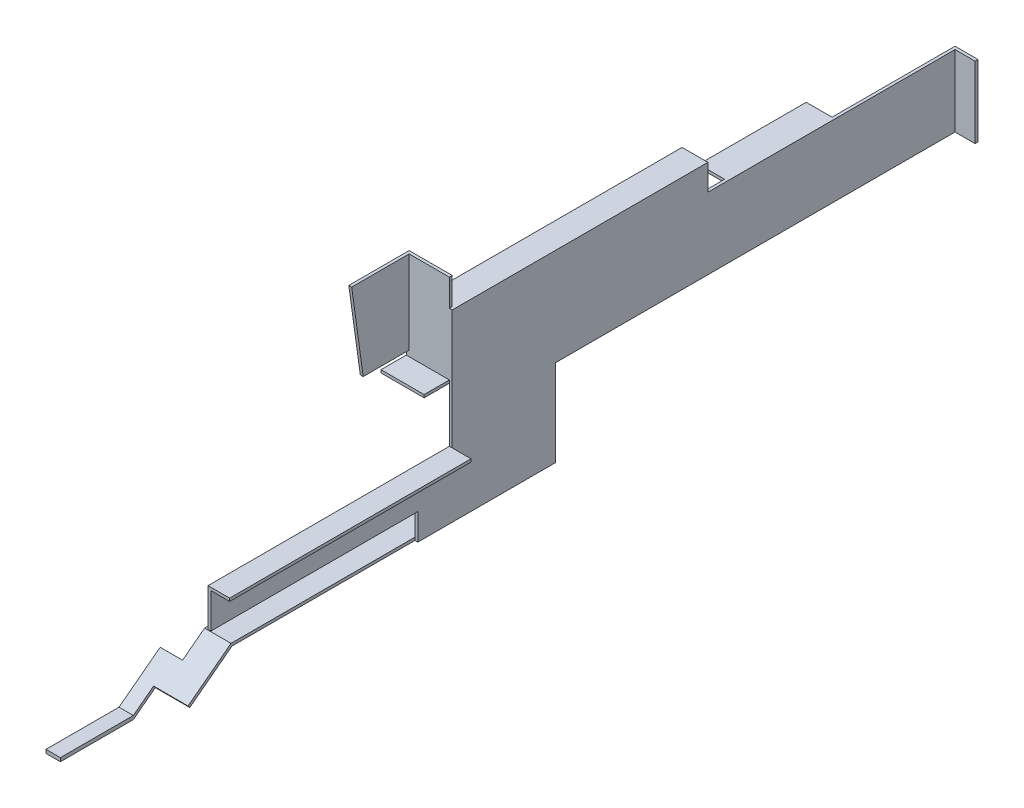
SolidWorks part; units mm, degrees
ref_plane "前视基准面" through (0, 0, 0) normal (0, 0, 1) x (1, 0, 0)
ref_plane "上视基准面" through (0, 0, 0) normal (0, 1, 0) x (1, 0, 0)
ref_plane "右视基准面" through (0, 0, 0) normal (1, 0, 0) x (0, 0, -1)
sketch "草图1" plane through (0, 0, 0) normal (1, 0, 0) x (0, 0, -1)
  line L1 (0, 0) -> (44, 0)
  line L2 (0, 0) -> (0, 6.22)
  line L3 (0, 6.22) -> (44, 6.22)
  line L4 (44, 0) -> (44, 6.22)
  line L5 (0, 0) -> (44, 6.22) construction
  line L6 (0, 6.22) -> (44, 0) construction
  point P4 (22, 3.11)
  dimension "D1" = 6.22
  dimension "D2" = 44
extrude "凸台-拉伸1" add sketch "草图1" along normal blind 0.25
sketch "草图2" plane through (0.25, 0, 0) normal (1, 0, 0) x (0, 0, -1)
  line L1 (44, 6.22) -> (43.75, 6.22)
  line L2 (44, 6.22) -> (44, 0)
  line L3 (44, 0) -> (43.75, 0)
  line L4 (43.75, 6.22) -> (43.75, 0)
  line L5 (44, 6.22) -> (43.75, 0) construction
  line L6 (44, 0) -> (43.75, 6.22) construction
  point P4 (43.875, 3.11)
  dimension "D1" = 0.25
extrude "凸台-拉伸2" add sketch "草图2" along normal blind 1.75
sketch "草图4" plane through (0, 0, 0) normal (-1, 0, 0) x (0, 0, 1)
  line L0 (-44, 6.22) -> (0, 6.22) construction
  line L1 (-44, 0) -> (-10, 0)
  line L2 (-44, 0) -> (-44, 0.25)
  line L3 (-44, 0.25) -> (-10, 0.25)
  line L4 (-10, 0) -> (-10, 0.25)
  line L5 (-44, 0) -> (-10, 0.25) construction
  line L6 (-44, 0.25) -> (-10, 0) construction
  line L7 (-33.3, 6.22) -> (-23.95, 6.22)
  line L8 (-33.3, 6.22) -> (-33.3, 5.97)
  line L9 (-33.3, 5.97) -> (-23.95, 5.97)
  line L10 (-23.95, 6.22) -> (-23.95, 5.97)
  line L11 (-33.3, 6.22) -> (-23.95, 5.97) construction
  line L12 (-33.3, 5.97) -> (-23.95, 6.22) construction
  line L13 (-44, 0) -> (-44, 6.22) construction
  point P4 (-27, 0.125)
  point P10 (-28.625, 6.095)
  dimension "D1" = 0.25
  dimension "D2" = 34
  dimension "D3" = 0.25
  dimension "D4" = 10.7
  dimension "D5" = 9.35
extrude "凸台-拉伸3" add sketch "草图4" along normal blind 2.25
sketch "草图5" plane through (0.25, 0, 0) normal (1, 0, 0) x (0, 0, -1)
  line L0 (43.75, 6.22) -> (0, 6.22) construction
  line L1 (22.25, 6.22) -> (0, 6.22)
  line L2 (22.25, 6.22) -> (22.25, 8.47)
  line L3 (22.25, 8.47) -> (0, 8.47)
  line L4 (0, 6.22) -> (0, 8.47)
  line L5 (22.25, 6.22) -> (0, 8.47) construction
  line L6 (22.25, 8.47) -> (0, 6.22) construction
  line L7 (44, 0) -> (44, 6.22) construction
  line L10 (0, 0) -> (9, 0)
  line L11 (0, 0) -> (0, -7.53)
  line L12 (0, -7.53) -> (9, -7.53)
  line L13 (9, 0) -> (9, -7.53)
  line L14 (0, 0) -> (9, -7.53) construction
  line L15 (0, -7.53) -> (9, 0) construction
  point P4 (11.125, 7.345)
  point P17 (4.5, -3.765)
  dimension "D1" = 21.75
  dimension "D2" = 2.25
  dimension "D3" = 16
  dimension "D4" = 35
extrude "凸台-拉伸4" add sketch "草图5" against normal blind 0.25
sketch "草图6" plane through (0.25, 0, 0) normal (1, 0, 0) x (0, 0, -1)
  line L0 (9, -7.53) -> (9, 0) construction
  line L1 (0, -7.53) -> (-21, -7.53)
  line L2 (0, -7.53) -> (0, -1.93)
  line L3 (0, -1.93) -> (-21, -1.93)
  line L4 (-21, -7.53) -> (-21, -1.93)
  line L5 (0, -7.53) -> (-21, -1.93) construction
  line L6 (0, -1.93) -> (-21, -7.53) construction
  point P4 (-10.5, -4.73)
  dimension "D1" = 30
  dimension "D2" = 5.6
extrude "凸台-拉伸5" add sketch "草图6" against normal blind 0.25
sketch "草图7" plane through (0.25, 0, 0) normal (1, 0, 0) x (0, 0, -1)
  line L0 (9, -7.53) -> (9, 0) construction
  line L1 (-21, -7.53) -> (-3, -7.53)
  line L2 (-21, -7.53) -> (-21, -5.23)
  line L3 (-21, -5.23) -> (-3, -5.23)
  line L4 (-3, -7.53) -> (-3, -5.23)
  line L5 (-21, -7.53) -> (-3, -5.23) construction
  line L6 (-21, -5.23) -> (-3, -7.53) construction
  line L7 (0, -1.93) -> (-21, -1.93) construction
  point P4 (-12, -6.38)
  dimension "D1" = 12
  dimension "D2" = 3.3
extrude "切除-拉伸1" cut sketch "草图7" against normal through all
sketch "草图8" plane through (0.25, 0, 0) normal (1, 0, 0) x (0, 0, -1)
  line L0 (-21, -1.93) -> (-21, -5.23) construction
  line L1 (0, -1.93) -> (-21, -1.93)
  line L2 (0, -1.93) -> (0, -2.18)
  line L3 (0, -2.18) -> (-21, -2.18)
  line L4 (-21, -1.93) -> (-21, -2.18)
  line L5 (0, -1.93) -> (-21, -2.18) construction
  line L6 (0, -2.18) -> (-21, -1.93) construction
  point P4 (-10.5, -2.055)
  dimension "D1" = 0.25
extrude "凸台-拉伸6" add sketch "草图8" along normal blind 1.63
sketch "草图9" plane through (0, 0, 0) normal (-1, 0, 0) x (0, 0, 1)
  line L1 (-9, -7.53) -> (19, -7.53)
  line L2 (-9, -7.53) -> (-9, -7.28)
  line L3 (-9, -7.28) -> (19, -7.28)
  line L4 (19, -7.53) -> (19, -7.28)
  line L5 (-9, -7.53) -> (19, -7.28) construction
  line L6 (-9, -7.28) -> (19, -7.53) construction
  point P4 (5, -7.405)
  dimension "D1" = 0.25
  dimension "D2" = 28
extrude "凸台-拉伸7" add sketch "草图9" along normal blind 2.3
sketch "草图10" plane through (-2.3, 0, 0) normal (-1, 0, 0) x (0, 0, 1)
  line L0 (19, -7.28) -> (24.5, -11.4658)
  line L1 (18.9157, -7.53) -> (24.5, -11.78)
  line L2 (-9, -7.53) -> (19, -7.53) construction
  line L3 (24.5, -11.4658) -> (24.5, -11.78)
  line L4 (19, -7.53) -> (19, -7.28) construction
  line L5 (19, -7.28) -> (-9, -7.28) construction
  line L6 (19, -7.28) -> (19, -7.53)
  line L7 (19, -7.53) -> (18.9157, -7.53)
  dimension "D1" = 0.25
  dimension "D2" = 5.5
  dimension "D3" = 4.5
extrude "凸台-拉伸8" add sketch "草图10" against normal blind 2.3
sketch "草图11" plane through (-2.3, 0, 0) normal (-1, 0, 0) x (0, 0, 1)
  line L0 (24.5, -11.4658) -> (20.9191, -8.7406)
  line L1 (24.5, -11.4658) -> (30.85, -11.4658)
  line L3 (24.5, -11.78) -> (30.85, -11.78)
  line L4 (30.85, -11.4658) -> (30.85, -11.78)
  line L5 (24.5, -11.4658) -> (30.85, -11.78) construction
  line L6 (24.5, -11.78) -> (30.85, -11.4658) construction
  line L7 (24.5, -11.4658) -> (19, -7.28) construction
  line L8 (20.9191, -8.7406) -> (20.7677, -8.9395)
  line L9 (18.9157, -7.53) -> (24.5, -11.78) construction
  line L10 (20.7677, -8.9395) -> (24.5, -11.78)
  point P4 (27.675, -11.6229)
  dimension "D1" = 6.35
  dimension "D2" = 4.5
extrude "凸台-拉伸9" add sketch "草图11" along normal offset from surface (1.95 mm away) 4.5 up to face at (0.25, -0.1869, -7.8462)
sketch "草图12" plane through (0, 4.5467, 3.4603) normal (0, 0.7958, 0.6056) x (1, 0, 0)
  line L0 (-2.3, -19.5283) -> (0, -19.5283) construction
  line L1 (0, -26.6302) -> (-2.3, -26.6302)
  line L2 (0, -26.6302) -> (0, -24.2283)
  line L3 (0, -24.2283) -> (-2.3, -24.2283)
  line L4 (-2.3, -26.6302) -> (-2.3, -24.2283)
  line L5 (0, -26.6302) -> (-2.3, -24.2283) construction
  line L6 (0, -24.2283) -> (-2.3, -26.6302) construction
  point P4 (-1.15, -25.4292)
  dimension "D1" = 4.7
extrude "切除-拉伸2" cut sketch "草图12" against normal through all
sketch "草图13" plane through (0, -11.4658, 0) normal (0, 1, 0) x (1, 0, 0)
  line L0 (-4.25, -24.5) -> (-4.25, -20.9191) construction
  line L1 (-2.3, -30.85) -> (-3, -30.85)
  line L2 (-2.3, -30.85) -> (-2.3, -22.7401)
  line L3 (-2.3, -22.7401) -> (-3, -22.7401)
  line L4 (-3, -30.85) -> (-3, -22.7401)
  line L5 (-2.3, -30.85) -> (-3, -22.7401) construction
  line L6 (-2.3, -22.7401) -> (-3, -30.85) construction
  point P4 (-2.65, -26.795)
  dimension "D1" = 1.25
extrude "切除-拉伸3" cut sketch "草图13" against normal through all and the other way through all
sketch "草图14" plane through (-2.3, 0, 0) normal (1, 0, 0) x (0, 0, -1)
  line L3 (-22.7401, -10.1264) -> (-22.7401, -10.4406)
  line L4 (-22.7401, -10.4406) -> (-22.5886, -10.3253)
  line L5 (-22.5886, -10.3253) -> (-22.7401, -10.1264)
  line L6 (-22.7401, -10.1264) -> (-22.7401, -10.4406)
  line L7 (-22.7401, -10.4406) -> (-22.5886, -10.3253)
  line L8 (-22.5886, -10.3253) -> (-22.7401, -10.1264)
  dimension "D1" = 0
extrude "切除-拉伸4" cut sketch "草图14" against normal up to surface (0.7 mm away) up to face at (-3, -11.1764, 26.03)
sketch "草图15" plane through (0, 0, 0) normal (-1, 0, 0) x (0, 0, 1)
  line L0 (0, 8.47) -> (0, -1.93) construction
  line L1 (-22.25, 8.47) -> (0, 8.47)
  line L2 (-22.25, 8.47) -> (-22.25, 8.22)
  line L3 (-22.25, 8.22) -> (0, 8.22)
  line L4 (0, 8.47) -> (0, 8.22)
  line L5 (-22.25, 8.47) -> (0, 8.22) construction
  line L6 (-22.25, 8.22) -> (0, 8.47) construction
  point P4 (-11.125, 8.345)
  dimension "D1" = 0.25
extrude "凸台-拉伸10" add sketch "草图15" along normal blind 2
sketch "草图16" plane through (0, 0, 0) normal (0, 0, 1) x (1, 0, 0)
  line L0 (0, 8.22) -> (0, 2.82)
  line L1 (0, 8.22) -> (0, -1.93) construction
  line L2 (0, 2.82) -> (-5, 2.82)
  line L3 (-5, 2.82) -> (-8.5, 10.82)
  line L4 (-8.5, 10.82) -> (0, 10.82)
  line L5 (0, 10.82) -> (0, 2.82)
  line L6 (0, -1.93) -> (1.88, -1.93) construction
  line M5 (0.25, 8.47) -> (-2, 8.47)
  line M6 (-2, 8.47) -> (-2, 8.22)
  line M7 (-2, 8.22) -> (0, 8.22)
  line M8 (0, 8.22) -> (0, -1.93)
  dimension "D1" = 4.75
  dimension "D2" = 8
  dimension "D3" = 5
  dimension "D4" = 8.5
extrude "凸台-拉伸11" add sketch "草图16" against normal blind 0.25 contours L5 L4 L3 L2 M8 M7 M6 M5
sketch "草图17" plane through (0, 0, 0) normal (0, 0, 1) x (1, 0, 0)
  line L0 (0, 2.82) -> (-5, 2.82) construction
  line L1 (-3.75, 2.82) -> (-8.5, 2.82)
  line L2 (-3.75, 2.82) -> (-3.75, 10.82)
  line L3 (-3.75, 10.82) -> (-8.5, 10.82)
  line L4 (-8.5, 2.82) -> (-8.5, 10.82)
  line L5 (-3.75, 2.82) -> (-8.5, 10.82) construction
  line L6 (-3.75, 10.82) -> (-8.5, 2.82) construction
  line L8 (0.25, 8.47) -> (0.25, -1.93) construction
  point P4 (-6.125, 6.82)
  dimension "D1" = 4
extrude "切除-拉伸5" cut sketch "草图17" against normal up to next
sketch "草图18" plane through (0, 0, 0) normal (0, 0, 1) x (1, 0, 0)
  line L0 (-3.75, 2.82) -> (-3.75, 10.82) construction
  line L1 (0, 2.82) -> (-3.75, 2.82)
  line L2 (0, 2.82) -> (0, 3.07)
  line L3 (0, 3.07) -> (-3.75, 3.07)
  line L4 (-3.75, 2.82) -> (-3.75, 3.07)
  line L5 (0, 2.82) -> (-3.75, 3.07) construction
  line L6 (0, 3.07) -> (-3.75, 2.82) construction
  point P4 (-1.875, 2.945)
  dimension "D1" = 0.25
extrude "凸台-拉伸12" add sketch "草图18" along normal blind 2.2
sketch "草图19" plane through (-3.75, 0, 0) normal (-1, 0, 0) x (0, 0, 1)
  line L0 (0, 10.82) -> (5, 10.82)
  line L1 (5, 10.82) -> (4, 3.57)
  line L2 (4, 3.57) -> (0, 3.57)
  line L3 (0, 3.07) -> (0, 10.82) construction
  line L4 (2.2, 3.07) -> (0, 3.07) construction
  line L5 (0, 10.82) -> (0, 3.57)
  dimension "D1" = 0.5
  dimension "D2" = 5
  dimension "D3" = 4
extrude "凸台-拉伸13" add sketch "草图19" against normal blind 0.25
